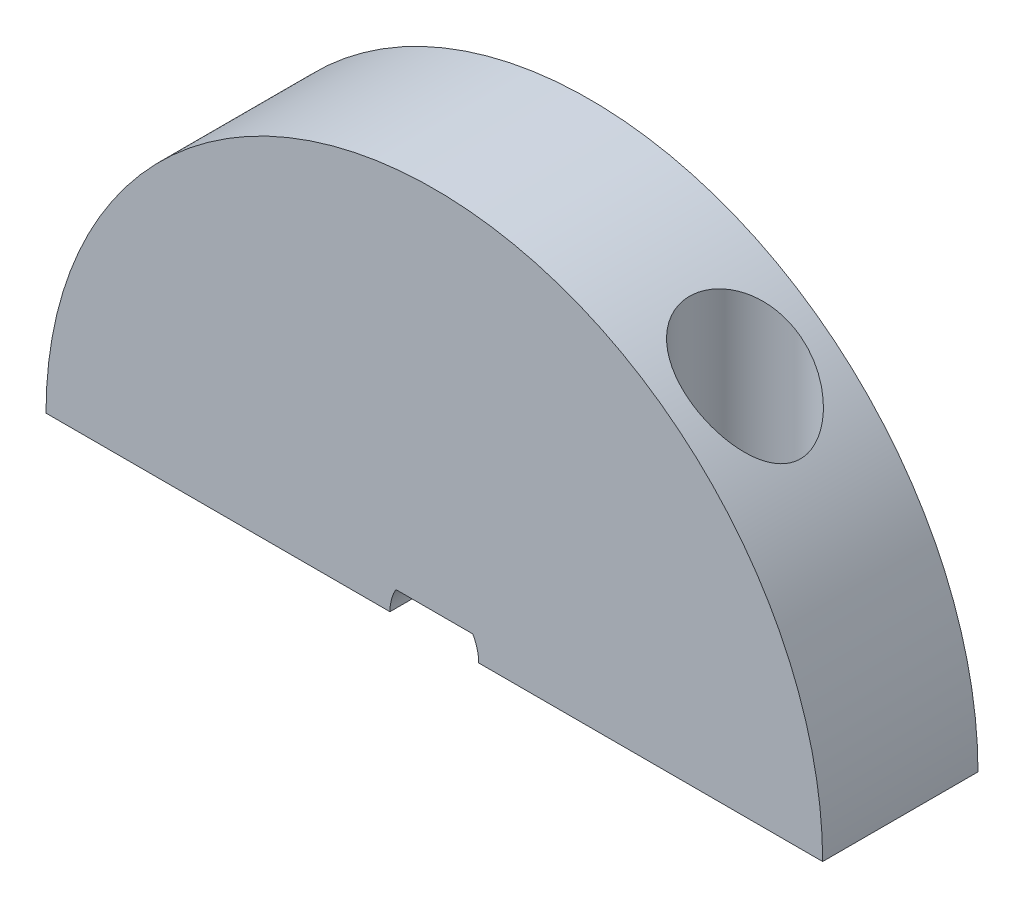
SolidWorks part; units mm, degrees
ref_plane "Plan de face" through (0, 0, 0) normal (0, 0, 1) x (1, 0, 0)
ref_plane "Plan de dessus" through (0, 0, 0) normal (0, 1, 0) x (1, 0, 0)
ref_plane "Plan de droite" through (0, 0, 0) normal (1, 0, 0) x (0, 0, -1)
sketch "Esquisse1" plane through (0, 0, 0) normal (0, 0, 1) x (1, 0, 0)
  line L0 (-1.7321, 1) -> (1.7321, 1)
  line L1 (0, 0) -> (17.5, 0)
  line L6 (17.5, 0) -> (-17.5, 0)
  circle A1 centre (0, 0) radius 2
  circle A2 centre (0, 0) radius 17.5
  dimension "D2" = 4
  dimension "D7" = 35
  dimension "D3" = 1
extrude "Boss.-Extru.1" add sketch "Esquisse1" along normal blind 5
sketch "Esquisse3" plane through (0, 0, 0) normal (0, 0, -1) x (-1, 0, 0)
  line L0 (0, 17.5) -> (0, -17.5)
  line L1 (-17.5, 0) -> (17.5, 0)
  circle A0 centre (0, 0) radius 17.5
  circle A1 centre (0, 0) radius 2
  arc M3 (1.7321, 1) -> (2, 0) centre (0, 0) cw
  arc M5 (17.5, 0) -> (-17.5, 0) centre (0, 0) ccw
  line M9 (-17.5, 0) -> (-2, 0)
  arc M10 (-2, 0) -> (-1.7321, 1) centre (0, 0) cw
  line M11 (2, 0) -> (17.5, 0)
extrude "Boss.-Extru.3" add sketch "Esquisse3" along normal blind 2 contours A1 L0 M5 M9 M10 | A1 L0 M3 M11 M5
sketch "Esquisse5" plane through (0, 0, 0) normal (0, -1, 0) x (1, 0, 0)
  line L0 (2, 5) -> (17.5, 5) construction
  line L1 (-2, 5) -> (-17.5, 5) construction
  line L2 (-17.5, 5) -> (-17.5, -2) construction
  line L3 (17.5, 5) -> (17.5, -2) construction
  circle A0 centre (-10.5, 1.5) radius 0.5
  circle A1 centre (10.5, 1.5) radius 2.5
  dimension "D1" = 1
  dimension "D2" = 5
  dimension "D3" = 3.5
  dimension "D4" = 3.5
  dimension "D5" = 7
  dimension "D6" = 7
extrude "Enlèv. mat.-Extru.1" cut sketch "Esquisse5" against normal blind 2
sketch "Esquisse7" plane through (0, 2, 0) normal (0, -1, 0) x (1, 0, 0)
  circle A0 centre (10.5, 1.5) radius 2.5
extrude "Enlèv. mat.-Extru.2" cut sketch "Esquisse7" against normal through all
